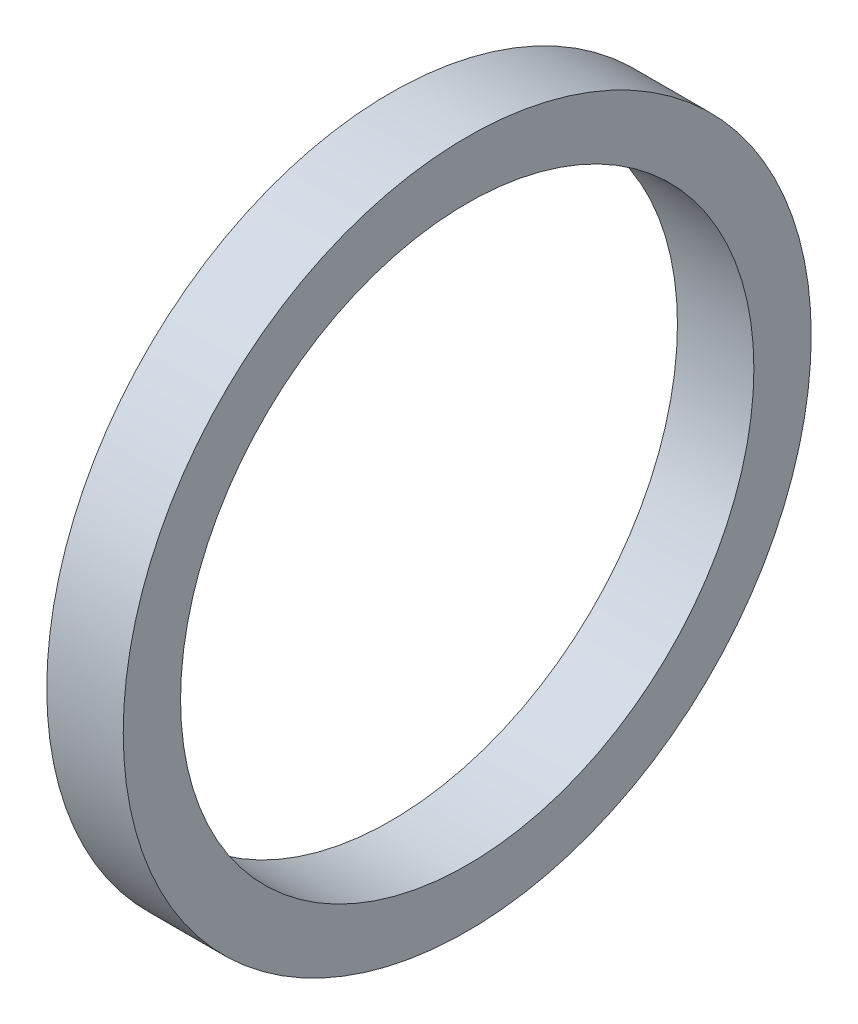
SolidWorks part; units mm, degrees
ref_plane "前视基准面" through (0, 0, 0) normal (0, 0, 1) x (1, 0, 0)
ref_plane "上视基准面" through (0, 0, 0) normal (0, 1, 0) x (1, 0, 0)
ref_plane "右视基准面" through (0, 0, 0) normal (1, 0, 0) x (0, 0, -1)
other "Configuration Table"
sketch "草图1" plane through (0, 0, 0) normal (0, 0, 1) x (1, 0, 0)
  line L0 (-59.6593, 0) -> (89.3294, 0) construction
  line L1 (0, 0) -> (0, 37.5)
  line L2 (0, 37.5) -> (10, 37.5)
  line L3 (10, 37.5) -> (10, 45)
  line L4 (10, 45) -> (0, 45)
  line L5 (0, 45) -> (0, 37.5)
  dimension "D1" = 37.5
  dimension "D2" = 7.5
  dimension "D3" = 10
revolve "旋转1" add sketch "草图1" angle 360 about L0
